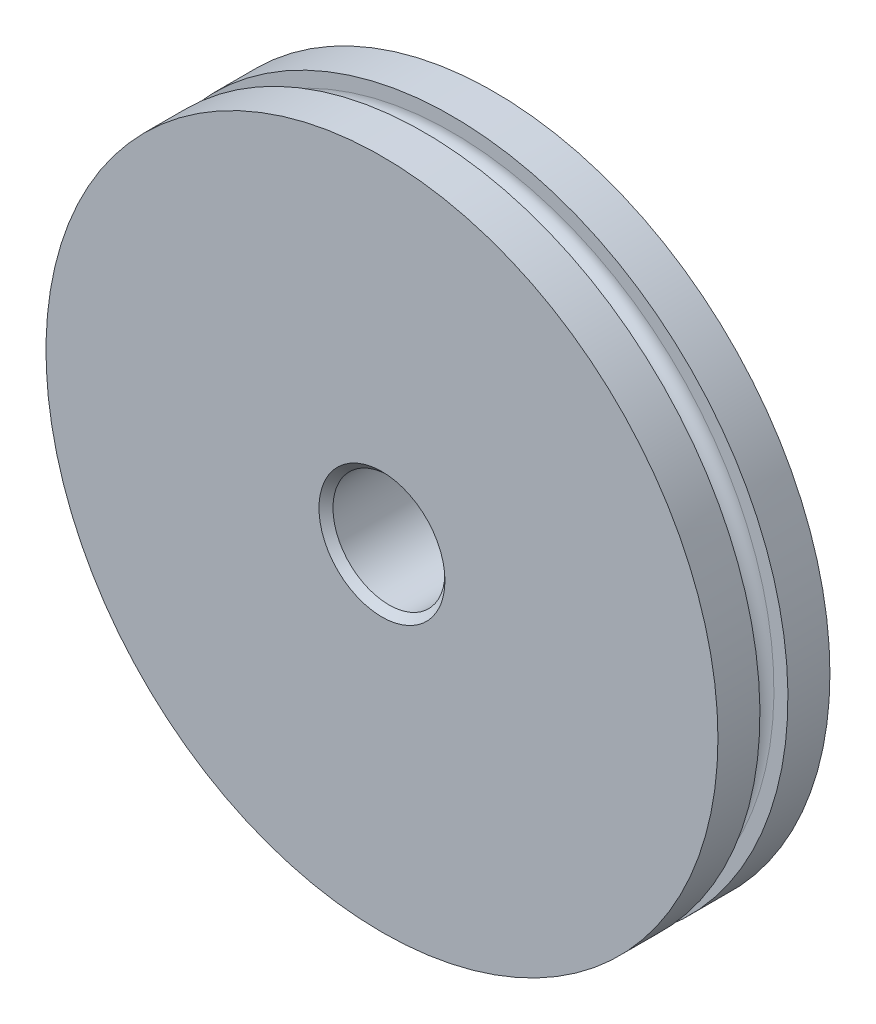
SolidWorks part; units mm, degrees
ref_plane "Front Plane" through (0, 0, 0) normal (0, 0, 1) x (1, 0, 0)
ref_plane "Top Plane" through (0, 0, 0) normal (0, 1, 0) x (1, 0, 0)
ref_plane "Right Plane" through (0, 0, 0) normal (1, 0, 0) x (0, 0, -1)
sketch "Sketch1" plane through (0, 0, 0) normal (0, 0, 1) x (1, 0, 0)
  circle A0 centre (0, 0) radius 38.1
  circle A1 centre (0, 0) radius 6.35
  dimension "D1" = 76.2
  dimension "D2" = 12.7
extrude "Extrude1" add sketch "Sketch1" along normal mid plane 12.7
sketch "Sketch2" plane through (0, 0, 0) normal (1, 0, 0) x (0, 0, -1)
  line L0 (-1.5875, 36.5125) -> (-1.5875, 38.1)
  line L1 (6.35, 38.1) -> (-6.35, 38.1) construction
  line L2 (1.5875, 36.5125) -> (1.5875, 38.1)
  line L3 (-1.5875, 38.1) -> (1.5875, 38.1)
  line L4 (0, 36.5125) -> (0, 0) construction
  line L5 (-6.35, 0) -> (6.35, 0) construction
  line L6 (-6.35, 38.1) -> (-6.35, -38.1) construction
  line L7 (6.35, -38.1) -> (6.35, 38.1) construction
  arc A0 (-1.5875, 36.5125) -> (1.5875, 36.5125) centre (0, 36.5125) ccw
  circle A1 centre (0, 36.5125) radius 1.5875 construction
  dimension "D1" = 3.175
  dimension "D2" = 1.5875
chamfer "Chamfer1" distance 0.7937 angle 45 2 edges at (6.35, 0, -6.35) (6.35, 0, 6.35)
revolve "Cut-Revolve1" cut sketch "Sketch2" angle 360 about L5
